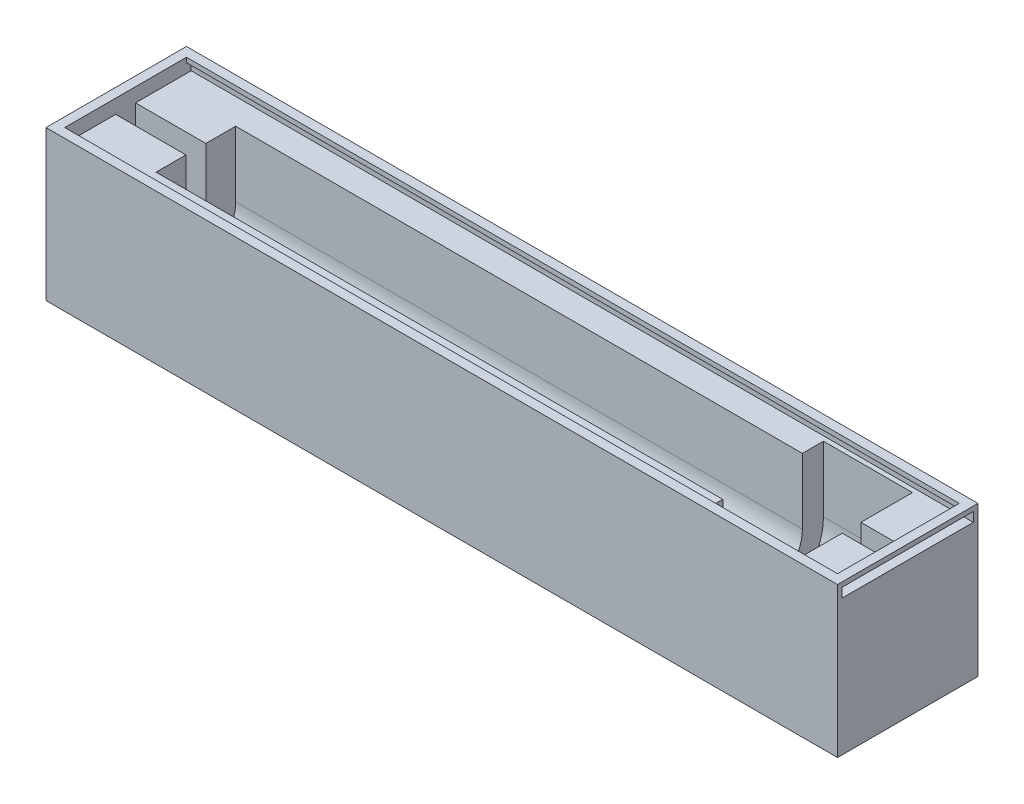
SolidWorks part; units mm, degrees
ref_plane "Front Plane" through (0, 0, 0) normal (0, 0, 1) x (1, 0, 0)
ref_plane "Top Plane" through (0, 0, 0) normal (0, 1, 0) x (1, 0, 0)
ref_plane "Right Plane" through (0, 0, 0) normal (1, 0, 0) x (0, 0, -1)
sketch "Sketch2" plane through (0, 0, 0) normal (1, 0, 0) x (0, 0, -1)
  line L0 (-13, 0) -> (-13, 17)
  line L1 (-13, 17) -> (-15, 17)
  line L2 (-15, 17) -> (-15, -15)
  line L3 (13, 0) -> (13, 17)
  line L4 (13, 17) -> (15, 17)
  line L5 (15, 17) -> (15, -15)
  line L6 (-15, -15) -> (15, -15)
  arc A0 (-13, 0) -> (13, 0) centre (0, 0) ccw
  dimension "D1" = 26
  dimension "D2" = 2
  dimension "D3" = 2
  dimension "D4" = 15
  dimension "D5" = 17
  dimension "D6" = 17
extrude "Boss-Extrude1" add sketch "Sketch2" along normal blind 165
sketch "Sketch3" plane through (165, 0, 0) normal (1, 0, 0) x (0, 0, -1)
  line L1 (-15, -15) -> (15, -15)
  line L2 (-15, -15) -> (-15, 17)
  line L3 (-15, 17) -> (15, 17)
  line L4 (15, -15) -> (15, 17)
extrude "Boss-Extrude2" add sketch "Sketch3" along normal blind 2
sketch "Sketch4" plane through (0, 0, 0) normal (-1, 0, 0) x (0, 0, 1)
  line L1 (-15, -15) -> (15, -15)
  line L2 (-15, -15) -> (-15, 17)
  line L3 (-15, 17) -> (15, 17)
  line L4 (15, -15) -> (15, 17)
extrude "Boss-Extrude3" add sketch "Sketch4" along normal blind 2
sketch "Sketch5" plane through (165, 0, 0) normal (-1, 0, 0) x (0, 0, 1)
  line L0 (-13, 17) -> (-13, 0)
  line L1 (-13, 17) -> (13, 17)
  line L2 (13, 17) -> (13, 0)
  arc A0 (13, 0) -> (-13, 0) centre (0, 0) cw
  arc A1 (-13, 0) -> (13, 0) centre (0, 0) ccw construction
extrude "Boss-Extrude4" add sketch "Sketch5" along normal blind 10
sketch "Sketch6" plane through (155, 0, 0) normal (-1, 0, 0) x (0, 0, 1)
  line L1 (-2, 0) -> (-2, 17)
  line L2 (13, 17) -> (-13, 17) construction
  line L3 (2, 0) -> (2, 17)
  line L4 (2, 17) -> (-2, 17)
  arc A0 (-2, 0) -> (2, 0) centre (0, 0) ccw
  dimension "D1" = 4
extrude "Cut-Extrude1" cut sketch "Sketch6" against normal blind 10
sketch "Sketch8" plane through (0, 0, 0) normal (1, 0, 0) x (0, 0, -1)
  line L0 (13, 0) -> (13, 17)
  line L1 (13, 17) -> (-13, 17)
  line L2 (-13, 17) -> (-13, 0)
  arc A0 (-13, 0) -> (13, 0) centre (0, 0) ccw
extrude "Boss-Extrude6" add sketch "Sketch8" along normal blind 15
sketch "Sketch9" plane through (15, 0, 0) normal (1, 0, 0) x (0, 0, -1)
  line L0 (-2.125, 0) -> (-2.125, 17)
  line L1 (13, 17) -> (-13, 17) construction
  line L2 (-2.125, 17) -> (2.125, 17)
  line L3 (2.125, 17) -> (2.125, 0)
  arc A0 (-2.125, 0) -> (2.125, 0) centre (0, 0) ccw
  dimension "D1" = 4.25
extrude "Cut-Extrude2" cut sketch "Sketch9" against normal blind 15
sketch "Sketch10" plane through (15, 0, 0) normal (1, 0, 0) x (0, 0, -1)
  line L0 (13, 0) -> (13, 17)
  line L1 (13, 17) -> (-13, 17)
  line L2 (-13, 17) -> (-13, 0)
  arc A0 (-13, 0) -> (13, 0) centre (0, 0) ccw
extrude "Boss-Extrude7" add sketch "Sketch10" along normal blind 121
sketch "Sketch11" plane through (136, 0, 0) normal (1, 0, 0) x (0, 0, -1)
  line L0 (-8.5, 0) -> (-8.5, 17)
  line L1 (13, 17) -> (-13, 17) construction
  line L2 (-8.5, 17) -> (8.5, 17)
  line L3 (8.5, 17) -> (8.5, 0)
  arc A0 (-8.5, 0) -> (8.5, 0) centre (0, 0) ccw
  dimension "D1" = 17
extrude "Cut-Extrude3" cut sketch "Sketch11" against normal blind 121
sketch "Sketch13" plane through (0, 17, 0) normal (0, 1, 0) x (1, 0, 0)
  line L1 (-2, -15) -> (167, -15)
  line L2 (-2, -15) -> (-2, 15)
  line L3 (-2, 15) -> (167, 15)
  line L4 (167, -15) -> (167, 15)
extrude "Cut-Extrude5" cut sketch "Sketch13" against normal blind 3
sketch "Sketch14" plane through (0, 14, 0) normal (0, 1, 0) x (1, 0, 0)
  line L1 (-2, -15) -> (167, -15)
  line L2 (-2, -15) -> (-2, 15)
  line L3 (-2, 15) -> (167, 15)
  line L4 (167, -15) -> (167, 15)
extrude "Boss-Extrude8" add sketch "Sketch14" along normal blind 3
sketch "Sketch12" plane through (167, 0, 0) normal (1, 0, 0) x (0, 0, -1)
  line L0 (15, -15) -> (15, 17) construction
  line L1 (-14, 16) -> (14, 16)
  line L2 (-14, 16) -> (-14, 14)
  line L3 (-14, 14) -> (14, 14)
  line L4 (14, 16) -> (14, 14)
  line L5 (-15, 17) -> (-15, -15) construction
  line L7 (-15, 17) -> (15, 17) construction
  dimension "D1" = 1
  dimension "D2" = 1
  dimension "D3" = 1
  dimension "D4" = 2
extrude "Cut-Extrude6" cut sketch "Sketch12" against normal blind 167
sketch "Sketch16" plane through (0, 17, 0) normal (0, 1, 0) x (1, 0, 0)
  line L0 (-2, -15) -> (167, -15) construction
  line L1 (0, 13) -> (165, 13)
  line L2 (0, 13) -> (0, -13)
  line L3 (0, -13) -> (165, -13)
  line L4 (165, 13) -> (165, -13)
  line L5 (167, 15) -> (-2, 15) construction
  line L6 (167, -15) -> (167, 15) construction
  line L7 (-2, 15) -> (-2, -15) construction
  dimension "D1" = 2
  dimension "D2" = 2
  dimension "D3" = 2
  dimension "D4" = 2
extrude "Cut-Extrude7" cut sketch "Sketch16" against normal blind 3
